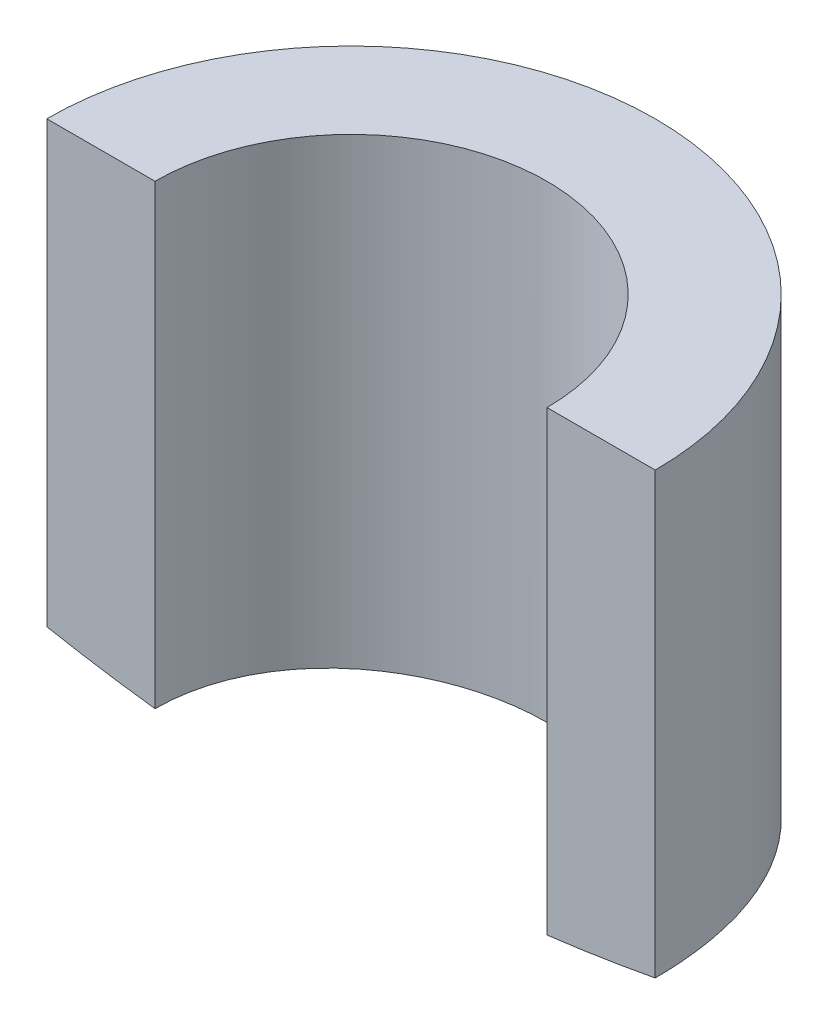
SolidWorks part; units mm, degrees
ref_plane "Front Plane" through (0, 0, 0) normal (0, 0, 1) x (1, 0, 0)
ref_plane "Top Plane" through (0, 0, 0) normal (0, 1, 0) x (1, 0, 0)
ref_plane "Right Plane" through (0, 0, 0) normal (1, 0, 0) x (0, 0, -1)
sketch "Sketch1" plane through (0, 0, 0) normal (0, 1, 0) x (1, 0, 0)
  line L0 (4.6, 0) -> (7.14, 0)
  line L1 (-4.6, 0) -> (-7.14, 0)
  arc A0 (4.6, 0) -> (-4.6, 0) centre (0, 0) ccw
  arc A1 (7.14, 0) -> (-7.14, 0) centre (0, 0) ccw
  circle A3 centre (0, 0) radius 4.6 construction
  circle A4 centre (0, 0) radius 7.14 construction
  point P1 (7.14, 0)
  point P7 (4.399, 1.3449)
  dimension "D1" = 9.2
  dimension "D2" = 2.54
extrude "Boss-Extrude1" add sketch "Sketch1" along normal blind 11
sketch "Sketch4" plane through (0, 0, 0) normal (0, 0, 1) x (1, 0, 0)
  line L0 (0, 0) -> (0, 38.1) construction
  line L1 (-4.6, 0) -> (4.6, 0) construction
  line L2 (-7.14, 0.675) -> (-7.14, 0)
  line L3 (-7.14, 11) -> (-7.14, 0) construction
  line L5 (7.14, 0) -> (7.14, 0.675)
  line L6 (-7.14, 0) -> (-7.14, -1.0636)
  line L7 (-7.14, -1.0636) -> (7.14, -1.0636)
  line L8 (7.14, -1.0636) -> (7.14, 0)
  arc A0 (-7.14, 0.675) -> (7.14, 0.675) centre (0, 38.1) ccw
  dimension "D2" = 76.2
  dimension "D1" = 38.1
extrude "Cut-Extrude1" cut sketch "Sketch4" against normal up to surface up to face at (0, 5.5, -3.57)
